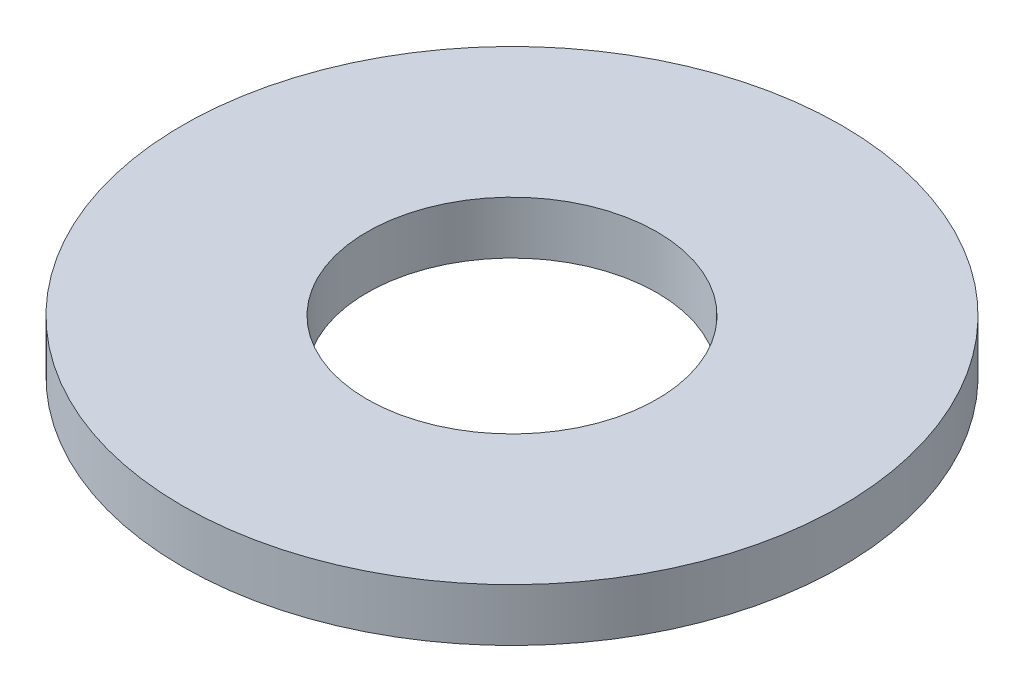
SolidWorks part; units mm, degrees
ref_plane "Front Plane" through (0, 0, 0) normal (0, 0, 1) x (1, 0, 0)
ref_plane "Top Plane" through (0, 0, 0) normal (0, 1, 0) x (1, 0, 0)
ref_plane "Right Plane" through (0, 0, 0) normal (1, 0, 0) x (0, 0, -1)
sketch "Sketch1" plane through (0, 0, 0) normal (0, 1, 0) x (1, 0, 0)
  circle A0 centre (-13.4903, 17.5468) radius 2.5
  circle A1 centre (-13.4903, 17.5468) radius 1.1
  dimension "D1" = 2.2
  dimension "D2" = 5
extrude "Boss-Extrude1" add sketch "Sketch1" along normal blind 0.4
